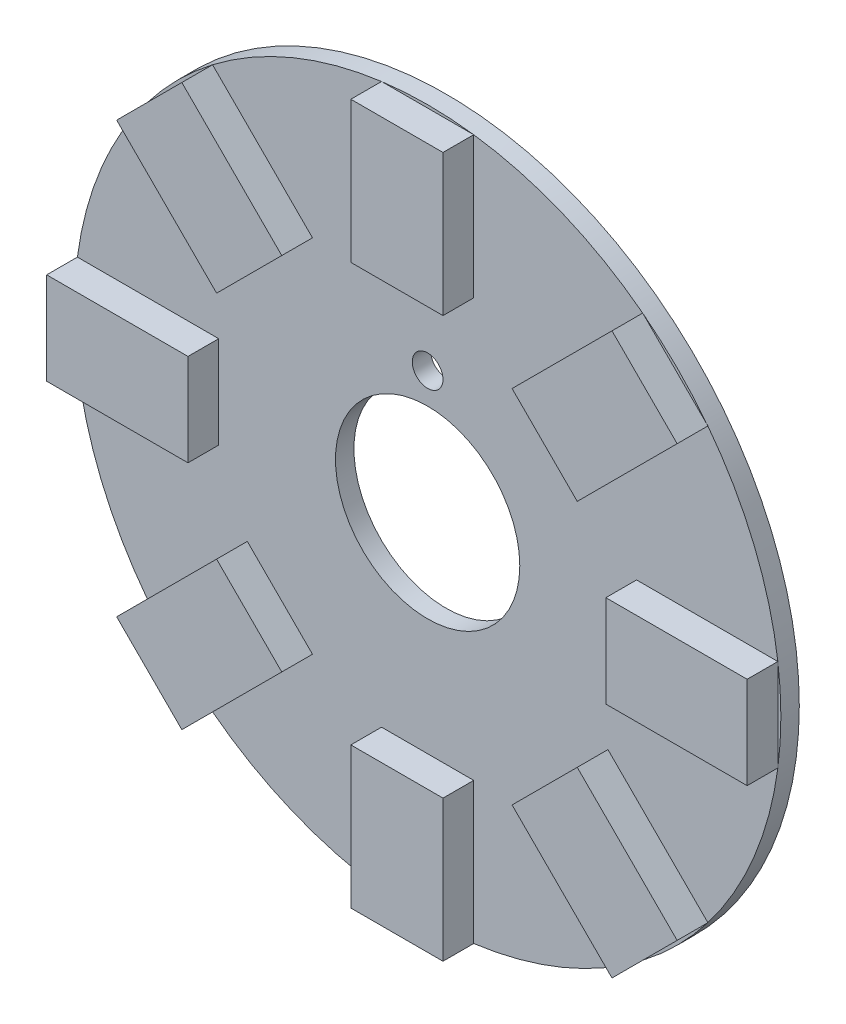
SolidWorks part; units mm, degrees
ref_plane "Piano frontale" through (0, 0, 0) normal (0, 0, 1) x (1, 0, 0)
ref_plane "Piano superiore" through (0, 0, 0) normal (0, 1, 0) x (1, 0, 0)
ref_plane "Piano destro" through (0, 0, 0) normal (1, 0, 0) x (0, 0, -1)
sketch "Schizzo1" plane through (0, 0, 0) normal (0, 0, 1) x (1, 0, 0)
  circle A0 centre (0, 0) radius 115
  dimension "D1" = 230
extrude "Estrusione1" add sketch "Schizzo1" along normal blind 6
sketch "Schizzo2" plane through (0, 0, 6) normal (0, 0, 1) x (1, 0, 0)
  line L1 (-15, 114.0175) -> (15, 114.0175)
  line L2 (-15, 114.0175) -> (-15, 68.0175)
  line L3 (-15, 68.0175) -> (15, 68.0175)
  line L4 (15, 114.0175) -> (15, 68.0175)
  line L5 (-15, 114.0175) -> (15, 68.0175) construction
  line L6 (-15, 68.0175) -> (15, 114.0175) construction
  circle A1 centre (0, 0) radius 115 construction
  point P0 (0, 91.0175)
  dimension "D1" = 46
  dimension "D2" = 30
extrude "Estrusione2" add sketch "Schizzo2" along normal blind 10
pattern_circular "RipetizioneCircolare1" count 8 over 360 about axis through (0, 0, 6) along (0, 0, -1) of "Estrusione2"
sketch "Schizzo4" plane through (0, 0, 6) normal (0, 0, 1) x (1, 0, 0)
  circle A0 centre (0, 0) radius 30
  dimension "D1" = 60
extrude "Estrusione3" cut sketch "Schizzo4" against normal through all
sketch "Schizzo5" plane through (0, 0, 6) normal (0, 0, 1) x (1, 0, 0)
  circle A0 centre (0, 40) radius 5
  dimension "D1" = 10
  dimension "D2" = 40
extrude "Estrusione4" cut sketch "Schizzo5" against normal through all
pattern_circular "RipetizioneCircolare2" [suppressed] count 4 over 360
